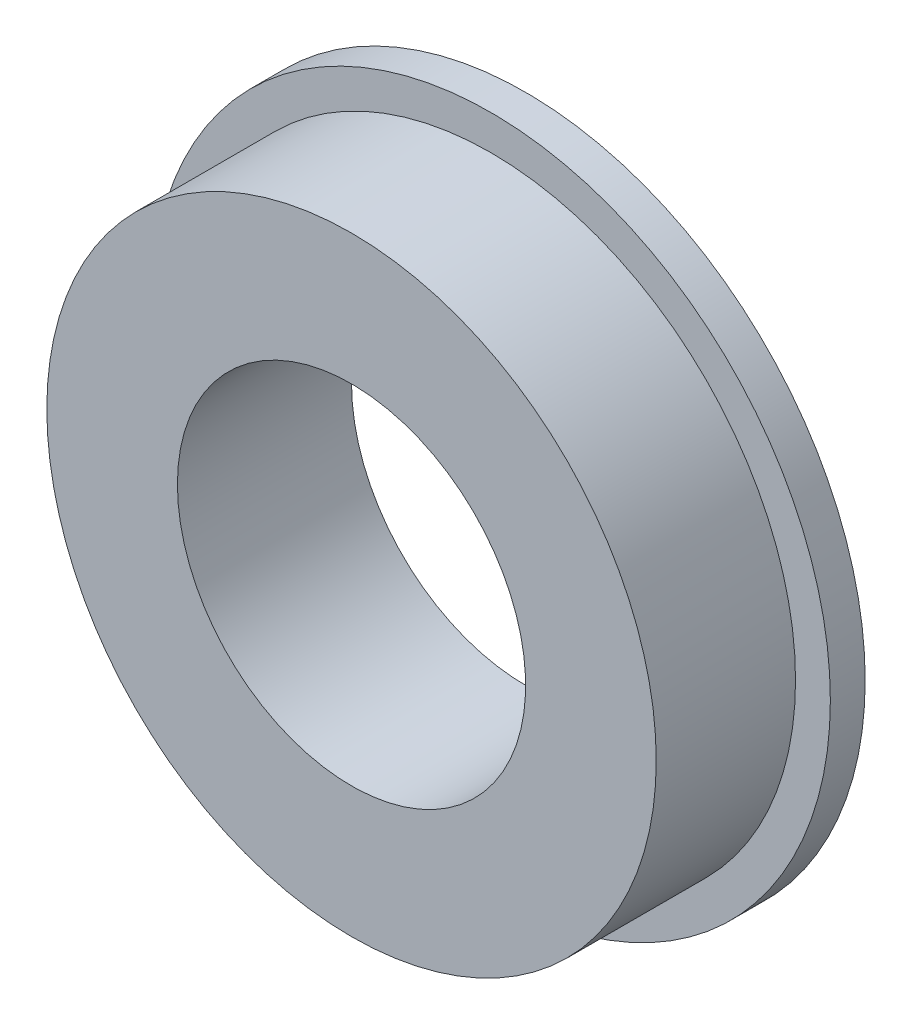
SolidWorks part; units mm, degrees
ref_plane "前视基准面" through (0, 0, 0) normal (0, 0, 1) x (1, 0, 0)
ref_plane "上视基准面" through (0, 0, 0) normal (0, 1, 0) x (1, 0, 0)
ref_plane "右视基准面" through (0, 0, 0) normal (1, 0, 0) x (0, 0, -1)
other "Configuration Table"
sketch "草图1" plane through (0, 0, 0) normal (0, 0, 1) x (1, 0, 0)
  circle A0 centre (0, 0) radius 7.8
  dimension "D1" = 15.6
extrude "凸台-拉伸1" add sketch "草图1" along normal blind 0.8
sketch "草图2" plane through (0, 0, 0.8) normal (0, 0, 1) x (1, 0, 0)
  circle A0 centre (0, 0) radius 7
  dimension "D1" = 14
extrude "凸台-拉伸2" add sketch "草图2" along normal blind 3.2
sketch "草图3" plane through (0, 0, 0) normal (0, 0, -1) x (-1, 0, 0)
  circle A0 centre (0, 0) radius 4
  dimension "D1" = 8
extrude "切除-拉伸1" cut sketch "草图3" against normal through all
